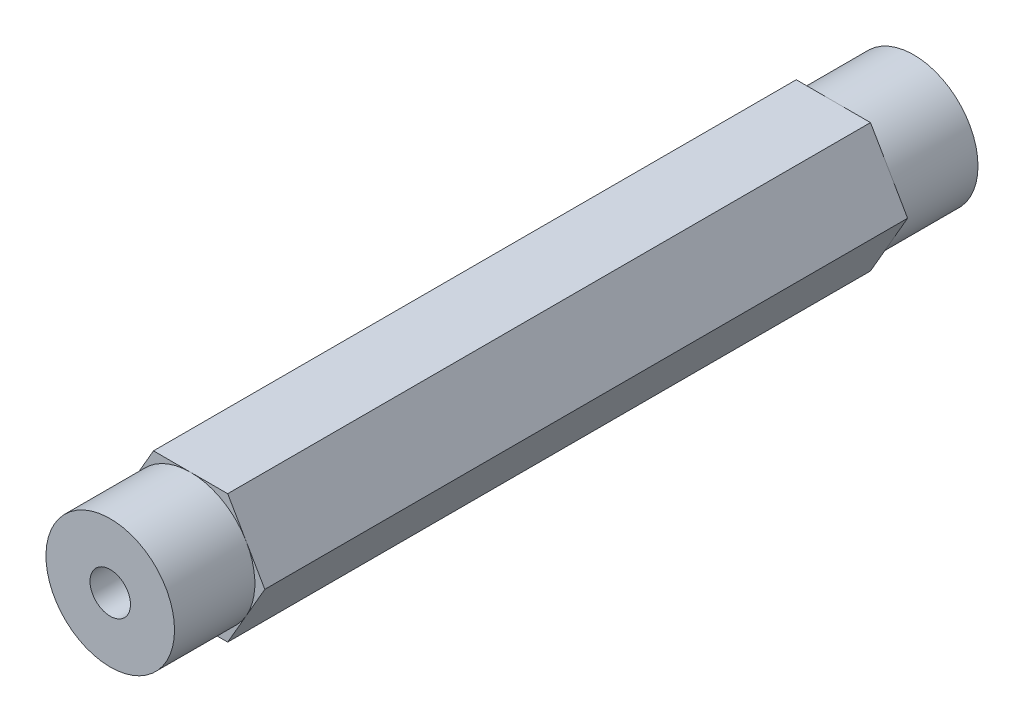
SolidWorks part; units mm, degrees
material "6061-T6 (SS)"
ref_plane "Front Plane" through (0, 0, 0) normal (0, 0, 1) x (1, 0, 0)
ref_plane "Top Plane" through (0, 0, 0) normal (0, 1, 0) x (1, 0, 0)
ref_plane "Right Plane" through (0, 0, 0) normal (1, 0, 0) x (0, 0, -1)
sketch "Sketch1" plane through (0, 0, 0) normal (0, 0, 1) x (1, 0, 0)
  line L1 (7.3323, 0) -> (3.6662, 6.35)
  line L2 (3.6662, 6.35) -> (-3.6662, 6.35)
  line L3 (-3.6662, 6.35) -> (-7.3323, 0)
  line L4 (-7.3323, 0) -> (-3.6662, -6.35)
  line L5 (-3.6662, -6.35) -> (3.6662, -6.35)
  line L6 (3.6662, -6.35) -> (7.3323, 0)
  circle A0 centre (0, 0) radius 6.35 construction
  circle A1 centre (0, 0) radius 6.875 construction
  circle A2 centre (0, 0) radius 2
  dimension "D1" = 12.7
  dimension "D2" = 13.75
  dimension "D3" = 4
extrude "Boss-Extrude1" add sketch "Sketch1" along normal mid plane 79.375 contours L1 A1 L2 L3 L4 L5 L6
ref_plane "Plane1" through (0, 0, 31.75) normal (0, 0, 1) x (1, 0, 0)
sketch "Sketch2" plane through (0, 0, 31.75) normal (0, 0, 1) x (1, 0, 0)
  circle A0 centre (0, 0) radius 6.35
  dimension "D1" = 12.7
extrude "Cut-Extrude-Thin1" cut sketch "Sketch2" along normal up to next thin
mirror "Mirror1" about plane through (0, 0, 0) normal (0, 0, 1) of "Cut-Extrude-Thin1"
equation "\"D2@Sketch1\"=13.75mm"
equation "\"D3@Sketch1\"=4mm"
